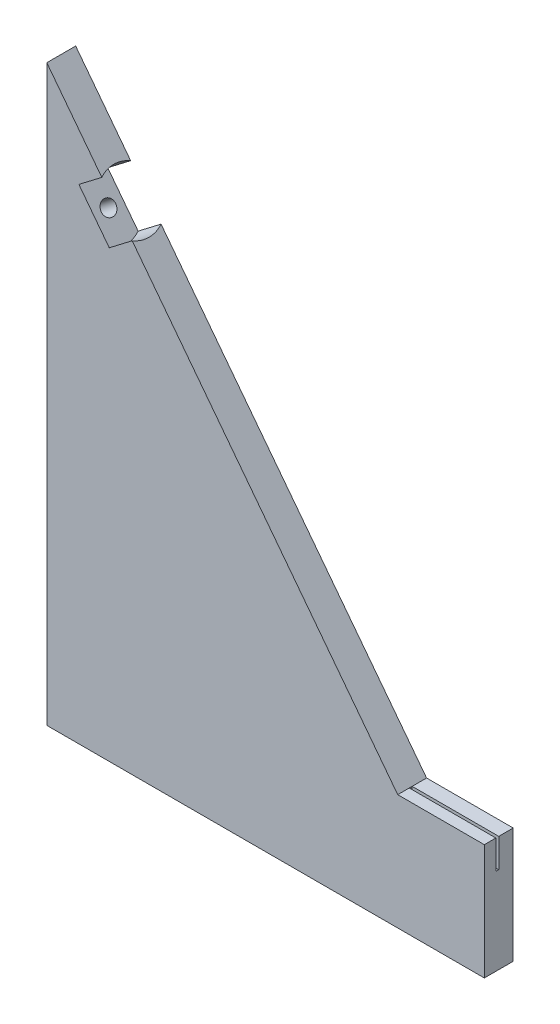
SolidWorks part; units mm, degrees
material "Brass"
ref_plane "Front Plane" through (0, 0, 0) normal (0, 0, 1) x (1, 0, 0)
ref_plane "Top Plane" through (0, 0, 0) normal (0, 1, 0) x (1, 0, 0)
ref_plane "Right Plane" through (0, 0, 0) normal (1, 0, 0) x (0, 0, -1)
sketch "Sketch1" plane through (0, 0, 0) normal (0, 0, 1) x (1, 0, 0)
  line L0 (-1000, 0) -> (49000, 0) construction
  line L1 (0, -1000) -> (0, 49000) construction
  line L2 (-15.4379, 32.8701) -> (-15.4379, -93.3802)
  line L3 (-15.4379, -93.3802) -> (61.7516, -93.3802)
  line L4 (61.7516, -67.9802) -> (80.8016, -67.9802)
  line L5 (61.7516, -67.9802) -> (-15.4379, 32.8701)
  line L6 (80.8016, -67.9802) -> (80.8016, -93.3802)
  line L7 (-938.2484, -67.9802) -> (49061.7516, -67.9802) construction
  line L8 (80.8016, -93.3802) -> (61.7516, -93.3802)
  dimension "D1" = 127
  dimension "D2" = 25.4
  dimension "D3" = 37.43
  dimension "D4" = 19.05
extrude "Extrude1" add sketch "Sketch1" along normal blind 6.35
sketch "Sketch3" plane through (0, -93.3802, 0) normal (0, -1, 0) x (1, 0, 0)
  line L0 (80.8016, 6.35) -> (80.8016, 0) construction
  line L1 (-2.0916, 3.175) -> (139.12, 3.175) construction
  line L2 (-15.4379, 0) -> (80.8016, 0) construction
  circle A0 centre (-8.0984, 3.175) radius 1.5875
  circle A1 centre (68.1016, 3.175) radius 1.5875
  dimension "D2" = 3.175
  dimension "D3" = 3.175
  dimension "D4" = 12.7
  dimension "D1" = 76.2
  dimension "D5" = 3.175
extrude "Extrude2" cut sketch "Sketch3" against normal blind 12.7
sketch "Sketch4" plane through (6.1296, 4.6915, 0) normal (0.7941, 0.6078, 0) x (0, 0, -1)
  line L0 (-1000, 0) -> (49000, 0) construction
  line L1 (-3.175, -1030.4896) -> (-3.175, 48969.5104) construction
  line L2 (-6.35, -91.515) -> (0, -91.515) construction
  line L3 (-6.35, -91.515) -> (-6.35, 35.485) construction
  circle A1 centre (-3.175, 10.085) radius 1.5875
  dimension "D4" = 3.175
  dimension "D1" = 3.175
  dimension "D2" = 101.6
extrude "Extrude3" cut sketch "Sketch4" against normal blind 12.7
sketch "Sketch6" plane through (0, -67.9802, 0) normal (0, 1, 0) x (1, 0, 0)
  line L0 (61.7516, -6.35) -> (61.7516, 0) construction
  line L1 (61.7516, -3.81) -> (80.8016, -3.81)
  line L2 (61.7516, -3.81) -> (61.7516, -3.175)
  line L3 (61.7516, -3.175) -> (80.8016, -3.175)
  line L4 (80.8016, -3.81) -> (80.8016, -3.175)
  line L5 (80.8016, -6.35) -> (80.8016, 0) construction
  line L6 (80.8016, 0) -> (61.7516, 0) construction
  dimension "D1" = 0.635
  dimension "D2" = 3.175
extrude "Extrude4" cut sketch "Sketch6" against normal blind 6.35
sketch "Sketch8" plane through (6.1296, 4.6915, 0) normal (0.7941, 0.6078, 0) x (0, 0, -1)
  line L0 (-3.175, -989.915) -> (-3.175, 49010.085) construction
  circle A0 centre (-3.175, 10.085) radius 6.35
  dimension "D1" = 12.7
extrude "Extrude5" cut sketch "Sketch8" against normal blind 6.35
